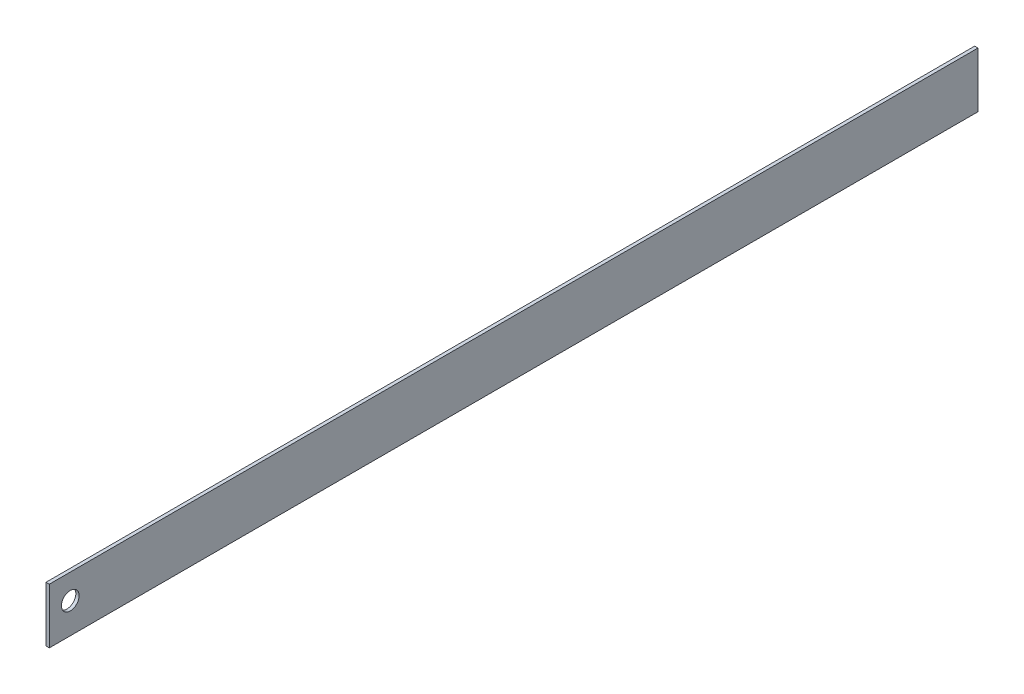
SolidWorks part; units mm, degrees
ref_plane "Front Plane" through (0, 0, 0) normal (0, 0, 1) x (1, 0, 0)
ref_plane "Top Plane" through (0, 0, 0) normal (0, 1, 0) x (1, 0, 0)
ref_plane "Right Plane" through (0, 0, 0) normal (1, 0, 0) x (0, 0, -1)
sketch "Sketch2" plane through (0, 0, 0) normal (1, 0, 0) x (0, 0, -1)
  line L1 (0, 0) -> (84.1, 0)
  line L2 (0, 0) -> (0, 5)
  line L3 (0, 5) -> (84.1, 5)
  line L4 (84.1, 0) -> (84.1, 5)
  circle A0 centre (1.8995, 2.755) radius 0.8
  dimension "D3" = 1.6
  dimension "D1" = 84.1
  dimension "D2" = 5
  dimension "D4" = 2.245
  dimension "D5" = 1.8995
extrude "Boss-Extrude1" add sketch "Sketch2" along normal blind 0.3
